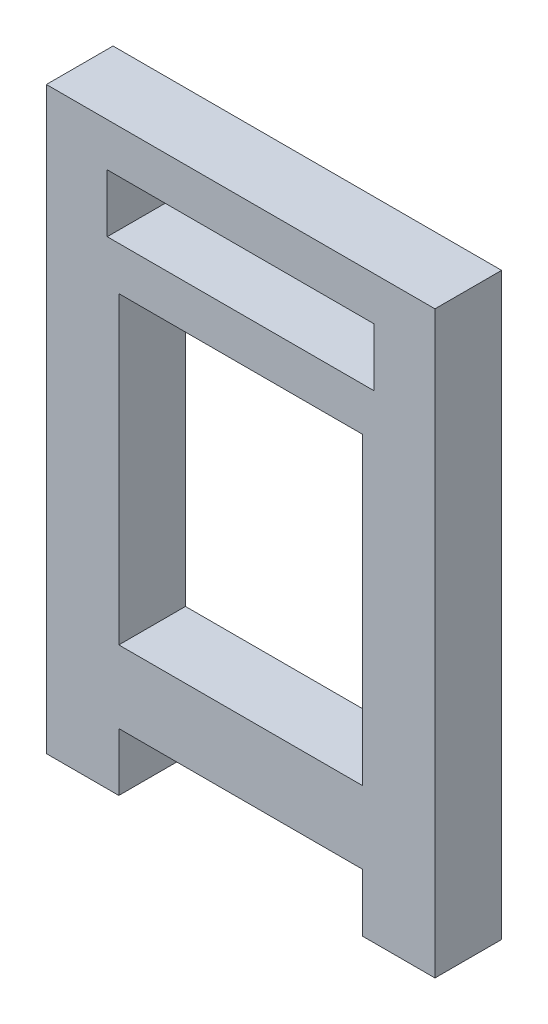
SolidWorks part; units mm, degrees
ref_plane "Front Plane" through (0, 0, 0) normal (0, 0, 1) x (1, 0, 0)
ref_plane "Top Plane" through (0, 0, 0) normal (0, 1, 0) x (1, 0, 0)
ref_plane "Right Plane" through (0, 0, 0) normal (1, 0, 0) x (0, 0, -1)
sketch "Sketch1" plane through (0, 0, 0) normal (0, 0, 1) x (1, 0, 0)
  line L0 (0, 0) -> (0, -2)
  line L1 (2.5, 0) -> (10.91, 0)
  line L2 (0, 0) -> (0, 18)
  line L3 (0, 18) -> (13.41, 18)
  line L4 (13.41, 0) -> (13.41, 18)
  line L5 (0, -2) -> (2.5, -2)
  line L6 (2.5, -2) -> (2.5, 0)
  line L7 (13.41, 0) -> (13.41, -2)
  line L8 (13.41, -2) -> (10.91, -2)
  line L9 (10.91, -2) -> (10.91, 0)
  line L12 (2.5, 2.5) -> (10.91, 2.5)
  line L13 (2.5, 2.5) -> (2.5, 13)
  line L14 (2.5, 13) -> (10.91, 13)
  line L15 (10.91, 2.5) -> (10.91, 13)
  line L16 (2.1, 14.5) -> (11.31, 14.5)
  line L17 (2.1, 14.5) -> (2.1, 16.5)
  line L18 (2.1, 16.5) -> (11.31, 16.5)
  line L19 (11.31, 14.5) -> (11.31, 16.5)
  dimension "D1" = 18
  dimension "D2" = 2.1
  dimension "D3" = 8.41
  dimension "D4" = 2
  dimension "D5" = 2
  dimension "D6" = 2.1
  dimension "D7" = 2.5
  dimension "D8" = 10.5
  dimension "D9" = 2
  dimension "D10" = 1.5
  dimension "D11" = 2.5
  dimension "D12" = 2.5
extrude "Boss-Extrude1" add sketch "Sketch1" along normal blind 2.3
